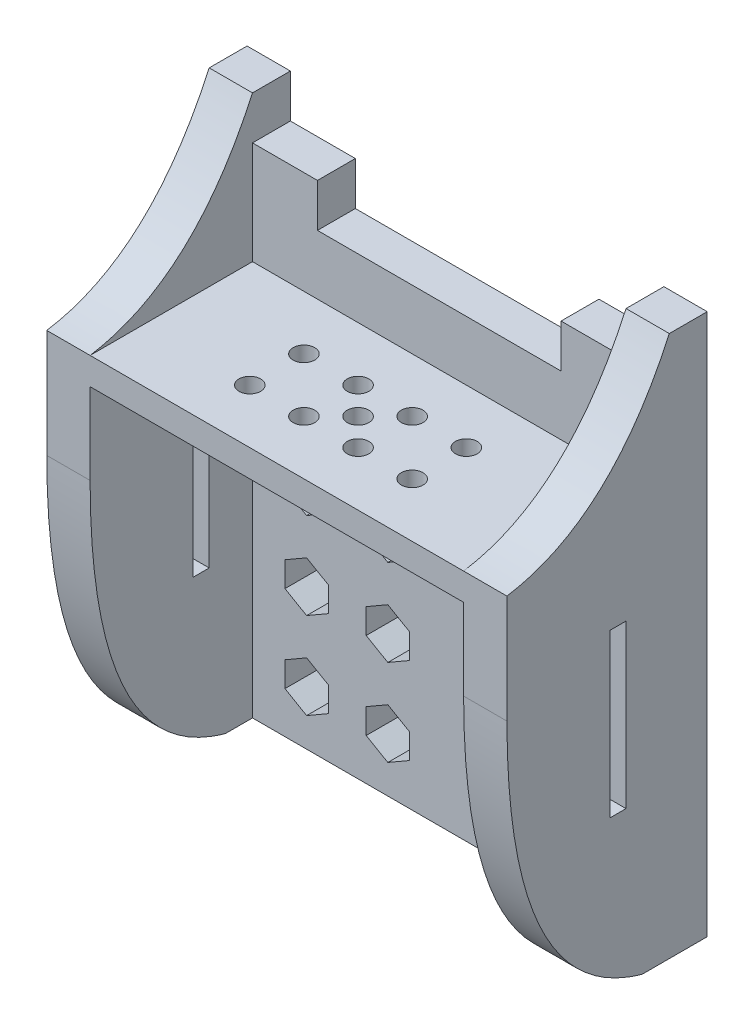
SolidWorks part; units mm, degrees
ref_plane "Alzado" through (0, 0, 0) normal (0, 0, 1) x (1, 0, 0)
ref_plane "Planta" through (0, 0, 0) normal (0, 1, 0) x (1, 0, 0)
ref_plane "Vista lateral" through (0, 0, 0) normal (1, 0, 0) x (0, 0, -1)
sketch "Croquis1" plane through (0, 0, 0) normal (0, 0, 1) x (1, 0, 0)
  line L0 (-42.5, 52) -> (-34.5, 52)
  line L1 (-34.5, 52) -> (-34.5, 44)
  line L2 (-34.5, 44) -> (-22.5, 44)
  line L3 (-22.5, 44) -> (-22.5, 36)
  line L4 (-22.5, 36) -> (22.5, 36)
  line L5 (-42.5, 52) -> (-42.5, -48)
  line L6 (-42.5, -48) -> (42.5, -48)
  line L7 (0, -48) -> (0, 36) construction
  line L8 (42.5, 52) -> (42.5, -48)
  line L9 (22.5, 44) -> (22.5, 36)
  line L10 (34.5, 44) -> (22.5, 44)
  line L11 (34.5, 52) -> (34.5, 44)
  line L12 (42.5, 52) -> (34.5, 52)
  dimension "D1" = 8
  dimension "D2" = 12
  dimension "D3" = 22.5
  dimension "D4" = 100
  dimension "D5" = 8
  dimension "D6" = 8
extrude "Saliente-Extruir1" add sketch "Croquis1" along normal blind 7
sketch "Croquis2" plane through (0, 0, 7) normal (0, 0, 1) x (1, 0, 0)
  line L0 (-42.5, 52) -> (-42.5, -48)
  line L1 (-34.5, 52) -> (-34.5, 25)
  line L2 (-34.5, 20) -> (-34.5, -48)
  line L3 (-42.5, -48) -> (42.5, -48) construction
  line L4 (-34.5, -48) -> (-42.5, -48)
  line L5 (-42.5, 52) -> (-34.5, 52)
  line L6 (0, 36) -> (0, -48) construction
  line L7 (22.5, 36) -> (-22.5, 36) construction
  line L8 (-34.5, 25) -> (34.5, 25)
  line L9 (-34.5, 20) -> (34.5, 20)
  line L10 (42.5, 52) -> (34.5, 52)
  line L11 (34.5, -48) -> (42.5, -48)
  line L12 (34.5, 20) -> (34.5, -48)
  line L13 (34.5, 52) -> (34.5, 25)
  line L14 (42.5, 52) -> (42.5, -48)
  point P18 (0, 20)
  point P19 (0, 25)
  dimension "D1" = 5
  dimension "D2" = 27
extrude "Saliente-Extruir2" add sketch "Croquis2" along normal blind 30
sketch "Croquis3" plane through (-42.5, 0, 0) normal (-1, 0, 0) x (0, 0, 1)
  line L0 (7, 52) -> (7, -48)
  line L1 (37, 52) -> (0, 52) construction
  line L2 (37, -48) -> (0, -48) construction
  line L3 (37, 25) -> (7, 25)
  line L12 (37, 20) -> (7, 20)
  line L14 (37, 25) -> (37, 20)
  line L15 (37, 20) -> (37, 5)
  line L19 (18, 10) -> (15, 10)
  line L20 (18, 10) -> (18, -20)
  line L21 (18, -20) -> (15, -20)
  line L22 (15, 10) -> (15, -20)
  line L23 (37, 52) -> (37, -48) construction
  line L25 (7, -48) -> (12, -48)
  spline S0 degree 2 poles (7, 52) (17.9721, 28.0036) (37, 25) knots 0 0 0 0.777512 0.777512 0.777512
  spline S1 degree 2 poles (37, 5) (36.9351, -41.1147) (12, -48) knots 0 0 0 0.740177 0.740177 0.740177
  line M14 (0, -48) -> (37, -48)
  line M15 (37, -48) -> (37, 52)
  line M16 (37, 52) -> (0, 52)
  dimension "D1" = 5
  dimension "D2" = 27
  dimension "D3" = 10
  dimension "D4" = 8
  dimension "D5" = 3
  dimension "D6" = 30
  dimension "D7" = 15
  dimension "D8" = 5
extrude "Cortar-Extruir3" cut sketch "Croquis3" against normal up to surface (85 mm away) contours S0 M16 M15 | S1 M15 M14 | L22 L21 L20 L19 up to face at (42.5, 2, 18.5)
sketch "Croquis4" plane through (0, 0, 7) normal (0, 0, 1) x (1, 0, 0)
  line L0 (0, 20) -> (0, -48) construction
  line L1 (-34.5, 20) -> (34.5, 20) construction
  line L2 (-34.5, -48) -> (34.5, -48) construction
  line L3 (-20.5, -38) -> (-28.5, -38) construction
  line L4 (-13.5, 12.3094) -> (-13.5, 7.6906)
  line L5 (-24.5, -10.6188) -> (-20.5, -8.3094)
  line L6 (-24.5, 5.3812) -> (-20.5, 7.6906)
  line L7 (-20.5, 7.6906) -> (-20.5, 12.3094)
  line L8 (-20.5, 12.3094) -> (-24.5, 14.6188)
  line L9 (-24.5, 14.6188) -> (-28.5, 12.3094)
  line L10 (-28.5, 12.3094) -> (-28.5, 7.6906)
  line L11 (-28.5, 7.6906) -> (-24.5, 5.3812)
  line L12 (-20.5, -8.3094) -> (-20.5, -3.6906)
  line L13 (-20.5, -3.6906) -> (-24.5, -1.3812)
  line L14 (-24.5, -1.3812) -> (-28.5, -3.6906)
  line L15 (-28.5, -3.6906) -> (-28.5, -8.3094)
  line L16 (-28.5, -8.3094) -> (-24.5, -10.6188)
  line L17 (-24.5, -26.6188) -> (-20.5, -24.3094)
  line L18 (-20.5, -24.3094) -> (-20.5, -19.6906)
  line L19 (-20.5, -19.6906) -> (-24.5, -17.3812)
  line L20 (-24.5, -17.3812) -> (-28.5, -19.6906)
  line L21 (-28.5, -19.6906) -> (-28.5, -24.3094)
  line L22 (-28.5, -24.3094) -> (-24.5, -26.6188)
  line L23 (-24.5, -42.6188) -> (-20.5, -40.3094)
  line L24 (-20.5, -40.3094) -> (-20.5, -35.6906)
  line L25 (-20.5, -35.6906) -> (-24.5, -33.3812)
  line L26 (-24.5, -33.3812) -> (-28.5, -35.6906)
  line L27 (-28.5, -35.6906) -> (-28.5, -40.3094)
  line L28 (-28.5, -40.3094) -> (-24.5, -42.6188)
  line L29 (-34.5, 20) -> (34.5, 20) construction
  line L31 (-13.5, 7.6906) -> (-9.5, 5.3812)
  line L32 (-9.5, 14.6188) -> (-13.5, 12.3094)
  line L33 (-5.5, 12.3094) -> (-9.5, 14.6188)
  line L34 (-5.5, 7.6906) -> (-5.5, 12.3094)
  line L35 (-9.5, 5.3812) -> (-5.5, 7.6906)
  line L36 (-9.5, -10.6188) -> (-5.5, -8.3094)
  line L37 (-5.5, -8.3094) -> (-5.5, -3.6906)
  line L38 (-5.5, -3.6906) -> (-9.5, -1.3812)
  line L39 (-9.5, -1.3812) -> (-13.5, -3.6906)
  line L40 (-13.5, -3.6906) -> (-13.5, -8.3094)
  line L41 (-13.5, -8.3094) -> (-9.5, -10.6188)
  line L42 (-9.5, -26.6188) -> (-5.5, -24.3094)
  line L43 (-5.5, -24.3094) -> (-5.5, -19.6906)
  line L44 (-5.5, -19.6906) -> (-9.5, -17.3812)
  line L45 (-9.5, -17.3812) -> (-13.5, -19.6906)
  line L46 (-13.5, -19.6906) -> (-13.5, -24.3094)
  line L47 (-13.5, -24.3094) -> (-9.5, -26.6188)
  line L48 (-9.5, -42.6188) -> (-5.5, -40.3094)
  line L49 (-5.5, -40.3094) -> (-5.5, -35.6906)
  line L50 (-5.5, -35.6906) -> (-9.5, -33.3812)
  line L51 (-9.5, -33.3812) -> (-13.5, -35.6906)
  line L52 (-13.5, -35.6906) -> (-13.5, -40.3094)
  line L53 (-13.5, -40.3094) -> (-9.5, -42.6188)
  line L54 (13.5, -40.3094) -> (9.5, -42.6188)
  line L55 (13.5, -35.6906) -> (13.5, -40.3094)
  line L56 (9.5, -33.3812) -> (13.5, -35.6906)
  line L57 (5.5, -35.6906) -> (9.5, -33.3812)
  line L58 (5.5, -40.3094) -> (5.5, -35.6906)
  line L59 (9.5, -42.6188) -> (5.5, -40.3094)
  line L60 (28.5, -40.3094) -> (24.5, -42.6188)
  line L61 (28.5, -35.6906) -> (28.5, -40.3094)
  line L62 (24.5, -33.3812) -> (28.5, -35.6906)
  line L63 (20.5, -35.6906) -> (24.5, -33.3812)
  line L64 (20.5, -40.3094) -> (20.5, -35.6906)
  line L65 (24.5, -42.6188) -> (20.5, -40.3094)
  line L66 (28.5, -24.3094) -> (24.5, -26.6188)
  line L67 (28.5, -19.6906) -> (28.5, -24.3094)
  line L68 (24.5, -17.3812) -> (28.5, -19.6906)
  line L69 (20.5, -19.6906) -> (24.5, -17.3812)
  line L70 (20.5, -24.3094) -> (20.5, -19.6906)
  line L71 (24.5, -26.6188) -> (20.5, -24.3094)
  line L72 (13.5, -24.3094) -> (9.5, -26.6188)
  line L73 (13.5, -19.6906) -> (13.5, -24.3094)
  line L74 (9.5, -17.3812) -> (13.5, -19.6906)
  line L75 (5.5, -19.6906) -> (9.5, -17.3812)
  line L76 (5.5, -24.3094) -> (5.5, -19.6906)
  line L77 (9.5, -26.6188) -> (5.5, -24.3094)
  line L78 (13.5, -8.3094) -> (9.5, -10.6188)
  line L79 (13.5, -3.6906) -> (13.5, -8.3094)
  line L80 (9.5, -1.3812) -> (13.5, -3.6906)
  line L81 (5.5, -3.6906) -> (9.5, -1.3812)
  line L82 (5.5, -8.3094) -> (5.5, -3.6906)
  line L83 (9.5, -10.6188) -> (5.5, -8.3094)
  line L84 (28.5, -8.3094) -> (24.5, -10.6188)
  line L85 (28.5, -3.6906) -> (28.5, -8.3094)
  line L86 (24.5, -1.3812) -> (28.5, -3.6906)
  line L87 (20.5, -3.6906) -> (24.5, -1.3812)
  line L88 (20.5, -8.3094) -> (20.5, -3.6906)
  line L89 (24.5, -10.6188) -> (20.5, -8.3094)
  line L90 (28.5, 7.6906) -> (24.5, 5.3812)
  line L91 (28.5, 12.3094) -> (28.5, 7.6906)
  line L92 (24.5, 14.6188) -> (28.5, 12.3094)
  line L93 (20.5, 12.3094) -> (24.5, 14.6188)
  line L94 (20.5, 7.6906) -> (20.5, 12.3094)
  line L95 (24.5, 5.3812) -> (20.5, 7.6906)
  line L96 (9.5, 14.6188) -> (13.5, 12.3094)
  line L97 (5.5, 12.3094) -> (9.5, 14.6188)
  line L98 (5.5, 7.6906) -> (5.5, 12.3094)
  line L99 (9.5, 5.3812) -> (5.5, 7.6906)
  line L100 (13.5, 7.6906) -> (9.5, 5.3812)
  line L101 (13.5, 12.3094) -> (13.5, 7.6906)
  line L102 (-34.5, -48) -> (-34.5, 20) construction
  circle A0 centre (-24.5, 10) radius 4 construction
  point P38 (-24.5, -38)
  dimension "D1" = 4
  dimension "D2" = 10
  dimension "D3" = 10
  dimension "D4" = 8
  dimension "D5" = 10
  dimension "D6" = 2
extrude "Cortar-Extruir4" cut sketch "Croquis4" against normal up to surface (7 mm away) up to face at (0, 30, 0)
sketch "Croquis5" plane through (0, 25, 0) normal (0, 1, 0) x (1, 0, 0)
  line L0 (0, -7) -> (0, -37) construction
  line L1 (22.5, -7) -> (-22.5, -7) construction
  line L2 (34.5, -37) -> (-34.5, -37) construction
  line L3 (-34.5, -22) -> (34.5, -22) construction
  line L4 (-34.5, -37) -> (-34.5, -7) construction
  line L5 (34.5, -7) -> (34.5, -37) construction
  circle A0 centre (0, -22) radius 2
  circle A1 centre (5, -17) radius 2
  circle A2 centre (5, -27) radius 2
  circle A3 centre (-5, -27) radius 2
  circle A4 centre (-5, -17) radius 2
  circle A5 centre (15, -17) radius 2
  circle A6 centre (15, -27) radius 2
  circle A7 centre (-15, -17) radius 2
  circle A8 centre (-15, -27) radius 2
  dimension "D1" = 5
  dimension "D5" = 10
  dimension "D2" = 5
  dimension "D3" = 5
  dimension "D4" = 5
  dimension "D6" = 10
extrude "Cortar-Extruir5" cut sketch "Croquis5" against normal up to surface (5 mm away) up to face at (0, 20, 22)
